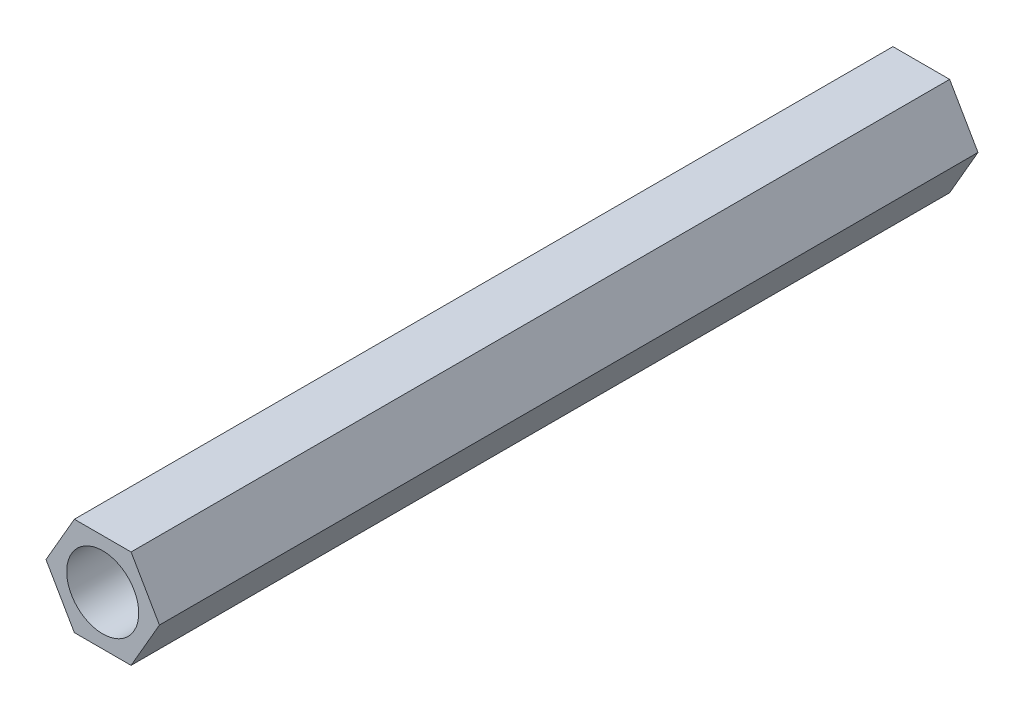
SolidWorks part; units mm, degrees
ref_plane "前视基准面" through (0, 0, 0) normal (0, 0, 1) x (1, 0, 0)
ref_plane "上视基准面" through (0, 0, 0) normal (0, 1, 0) x (1, 0, 0)
ref_plane "右视基准面" through (0, 0, 0) normal (1, 0, 0) x (0, 0, -1)
sketch "草图1" plane through (0, 0, 0) normal (0, 0, 1) x (1, 0, 0)
  line L1 (1.7321, 0) -> (0.866, 1.5)
  line L2 (0.866, 1.5) -> (-0.866, 1.5)
  line L3 (-0.866, 1.5) -> (-1.7321, 0)
  line L4 (-1.7321, 0) -> (-0.866, -1.5)
  line L5 (-0.866, -1.5) -> (0.866, -1.5)
  line L6 (0.866, -1.5) -> (1.7321, 0)
  circle A0 centre (0, 0) radius 1.5 construction
  dimension "D1" = 3
extrude "凸台-拉伸1" add sketch "草图1" along normal blind 25
sketch "草图2" plane through (0, 0, 25) normal (0, 0, 1) x (1, 0, 0)
  circle A0 centre (0, 0) radius 1.1
  dimension "D1" = 2.2
extrude "切除-拉伸1" cut sketch "草图2" against normal blind 3
sketch "草图3" plane through (0, 0, 0) normal (0, 0, -1) x (-1, 0, 0)
  circle A0 centre (0, 0) radius 1.1
  dimension "D1" = 2.2
extrude "切除-拉伸2" cut sketch "草图3" against normal blind 3
